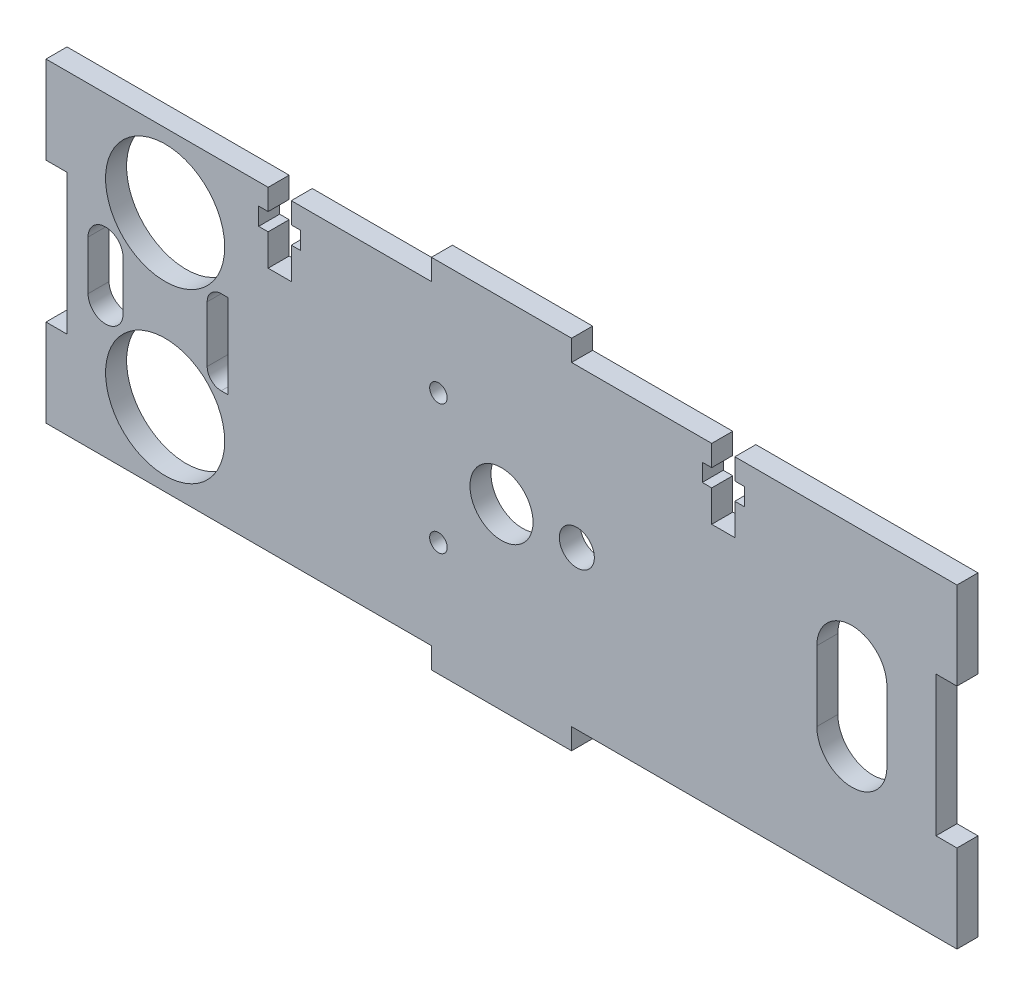
SolidWorks part; units mm, degrees
ref_plane "Front Plane" through (0, 0, 0) normal (0, 0, 1) x (1, 0, 0)
ref_plane "Top Plane" through (0, 0, 0) normal (0, 1, 0) x (1, 0, 0)
ref_plane "Right Plane" through (0, 0, 0) normal (1, 0, 0) x (0, 0, -1)
sketch "Sketch1" plane through (0, 0, 0) normal (0, 0, 1) x (1, 0, 0)
  line L0 (-10, -22.5) -> (-65, -22.5)
  line L1 (65, -22.5) -> (10, -22.5)
  line L2 (65, -22.5) -> (65, -10)
  line L3 (65, 22.5) -> (33.3, 22.5)
  line L4 (-65, -22.5) -> (-65, -10)
  line L5 (65, -22.5) -> (-65, 22.5) construction
  line L6 (65, 22.5) -> (-65, -22.5) construction
  line L8 (-10, -22.5) -> (-10, -25.5)
  line L9 (-10, -25.5) -> (10, -25.5)
  line L10 (10, -22.5) -> (10, -25.5)
  line L11 (0, -55) -> (0, 55) construction
  line L12 (-62, -10) -> (-65, -10)
  line L13 (-62, -10) -> (-62, 10)
  line L14 (-62, 10) -> (-65, 10)
  line L16 (-62, -10) -> (-65, 10) construction
  line L17 (-62, 10) -> (-65, -10) construction
  line L18 (62, 10) -> (65, 10)
  line L20 (62, -10) -> (65, -10)
  line L21 (62, -10) -> (62, 10)
  line L22 (-65, 10) -> (-65, 22.5)
  line L23 (65, 10) -> (65, 22.5)
  line L24 (-56.5, 3.5) -> (-56.5, -3.5) construction
  line L29 (-54, 3.5) -> (-54, -3.5)
  line L30 (-59, 3.5) -> (-59, -3.5)
  line L31 (-39, -6) -> (-40, -6)
  line L32 (-39, -6) -> (-39, 6)
  line L33 (-39, 6) -> (-40, 6)
  line L34 (-42, -4) -> (-42, 4)
  line L35 (-39, -6) -> (-42, 6) construction
  line L36 (-39, 6) -> (-42, -6) construction
  line L37 (55, 0) -> (-55, 0) construction
  line L40 (-10, 22.5) -> (-10, 25.5)
  line L41 (-10, 25.5) -> (10, 25.5)
  line L42 (10, 22.5) -> (10, 25.5)
  line L43 (-10, 22.5) -> (-30, 22.5)
  line L44 (33.3, 12.5) -> (30, 12.5)
  line L46 (-33.3, 22.5) -> (-33.3, 19.5)
  line L47 (-33.3, 12.5) -> (-30, 12.5)
  line L48 (-30, 22.5) -> (-30, 19.5)
  line L49 (-34.65, 19.5) -> (-33.3, 19.5)
  line L50 (-34.65, 19.5) -> (-34.65, 17)
  line L51 (-34.65, 17) -> (-33.3, 17)
  line L52 (-28.65, 19.5) -> (-28.65, 17)
  line L53 (30, 22.5) -> (30, 19.5)
  line L55 (33.3, 22.5) -> (33.3, 19.5)
  line L56 (34.65, 17) -> (33.3, 17)
  line L57 (28.65, 19.5) -> (28.65, 17)
  line L58 (34.65, 19.5) -> (33.3, 19.5)
  line L59 (34.65, 19.5) -> (34.65, 17)
  line L60 (-33.3, 22.5) -> (-65, 22.5)
  line L61 (-30, 19.5) -> (-28.65, 19.5)
  line L62 (-33.3, 17) -> (-33.3, 12.5)
  line L63 (-30, 17) -> (-28.65, 17)
  line L64 (-30, 17) -> (-30, 12.5)
  line L65 (30, 22.5) -> (10, 22.5)
  line L66 (30, 19.5) -> (28.65, 19.5)
  line L67 (30, 17) -> (30, 12.5)
  line L68 (33.3, 17) -> (33.3, 12.5)
  line L69 (30, 17) -> (28.65, 17)
  line L70 (50, -5) -> (50, 5) construction
  line L75 (45, -5) -> (45, 5)
  line L76 (55, -5) -> (55, 5)
  circle A0 centre (-48, 12) radius 8.5
  circle A1 centre (-48, -12) radius 8.5
  circle A6 centre (0, 0) radius 4.5
  circle A7 centre (10.75, 0) radius 2.5
  arc A10 (-54, 3.5) -> (-59, 3.5) centre (-56.5, 3.5) ccw
  arc A11 (-59, -3.5) -> (-54, -3.5) centre (-56.5, -3.5) ccw
  arc A12 (-40, -6) -> (-42, -4) centre (-40, -4) cw
  arc A13 (-40, 6) -> (-42, 4) centre (-40, 4) ccw
  circle A14 centre (-9, 9.25) radius 1.25
  circle A15 centre (-9, -9.25) radius 1.25
  arc A16 (45, -5) -> (55, -5) centre (50, -5) ccw
  arc A17 (55, 5) -> (45, 5) centre (50, 5) ccw
  point P0 (0, 0)
  point P10 (-63.5, 0)
  point P26 (-56.5, 0)
  point P49 (-40.5, 0)
  point P83 (50, 0)
  point P88 (0, 0)
  dimension "D8" = 17
  dimension "D15" = 2
  dimension "D16" = 9
  dimension "D17" = 5
  dimension "D22" = 2.5
  dimension "D12" = 2.5
  dimension "D35" = 5
  dimension "D1" = 130
  dimension "D2" = 45
  dimension "D3" = 3
  dimension "D4" = 20
  dimension "D5" = 55
  dimension "D6" = 20
  dimension "D7" = 3
  dimension "D9" = 17
  dimension "D10" = 24
  dimension "D11" = 12
  dimension "D13" = 7
  dimension "D14" = 6
  dimension "D18" = 10.75
  dimension "D19" = 3
  dimension "D20" = 12
  dimension "D21" = 6
  dimension "D23" = 9
  dimension "D24" = 9.25
  dimension "D25" = 20
  dimension "D26" = 3
  dimension "D27" = 55
  dimension "D28" = 3.3
  dimension "D29" = 10
  dimension "D30" = 2.5
  dimension "D31" = 6
  dimension "D32" = 3
  dimension "D33" = 1.35
  dimension "D34" = 20
  dimension "D36" = 10
  dimension "D37" = 10
extrude "Boss-Extrude1" add sketch "Sketch1" along normal blind 3
